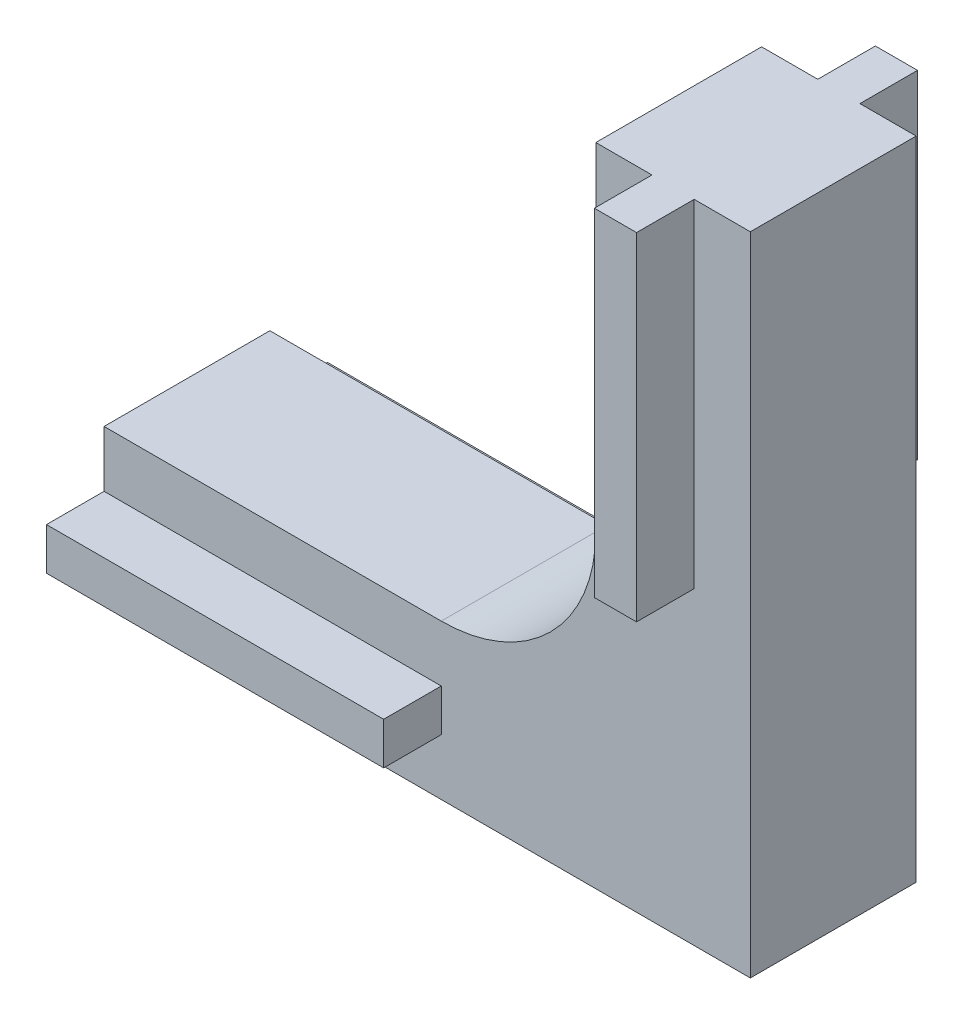
SolidWorks part; units mm, degrees
ref_plane "Front Plane" through (0, 0, 0) normal (0, 0, 1) x (1, 0, 0)
ref_plane "Top Plane" through (0, 0, 0) normal (0, 1, 0) x (1, 0, 0)
ref_plane "Right Plane" through (0, 0, 0) normal (1, 0, 0) x (0, 0, -1)
sketch "Sketch1" plane through (0, 0, 0) normal (0, 0, 1) x (1, 0, 0)
  line L0 (0, 5.5) -> (12, 5.5)
  line L1 (0, 0) -> (23, 0)
  line L2 (0, 0) -> (0, 5.5)
  line L3 (17.5, 23) -> (23, 23)
  line L4 (23, 0) -> (23, 23)
  line L5 (17.5, 11) -> (17.5, 23)
  arc A0 (12, 5.5) -> (17.5, 11) centre (12, 11) ccw
  dimension "D1" = 23
  dimension "D2" = 23
  dimension "D3" = 5.5
  dimension "D4" = 5.5
  dimension "D5" = 12
  dimension "D6" = 12
extrude "Boss-Extrude1" add sketch "Sketch1" along normal blind 5.9
sketch "Sketch2" plane through (0, 0, 5.9) normal (0, 0, 1) x (1, 0, 0)
  line L0 (0, 5.5) -> (0, 0) construction
  line L1 (0, 3.5) -> (12, 3.5)
  line L2 (0, 3.5) -> (0, 2)
  line L3 (0, 2) -> (12, 2)
  line L4 (12, 3.5) -> (12, 2)
  line L5 (12, 5.5) -> (0, 5.5) construction
  line L6 (0, 0) -> (23, 0) construction
  line L7 (23, 0) -> (11.807, 11.193) construction
  line L8 (19.5, 23) -> (21, 23)
  line L9 (21, 23) -> (21, 11)
  line L10 (19.5, 11) -> (21, 11)
  line L11 (19.5, 23) -> (19.5, 11)
  dimension "D1" = 2
  dimension "D2" = 2
  dimension "D3" = 12
  dimension "D4" = 15.8293
  dimension "D5" = 45
extrude "Boss-Extrude2" add sketch "Sketch2" along normal blind 2.05
ref_plane "Plane1" through (0, 0, 2.95) normal (0, 0, 1) x (1, 0, 0)
mirror "Mirror1" about plane through (0, 0, 2.95) normal (0, 0, 1) of "Boss-Extrude2"
